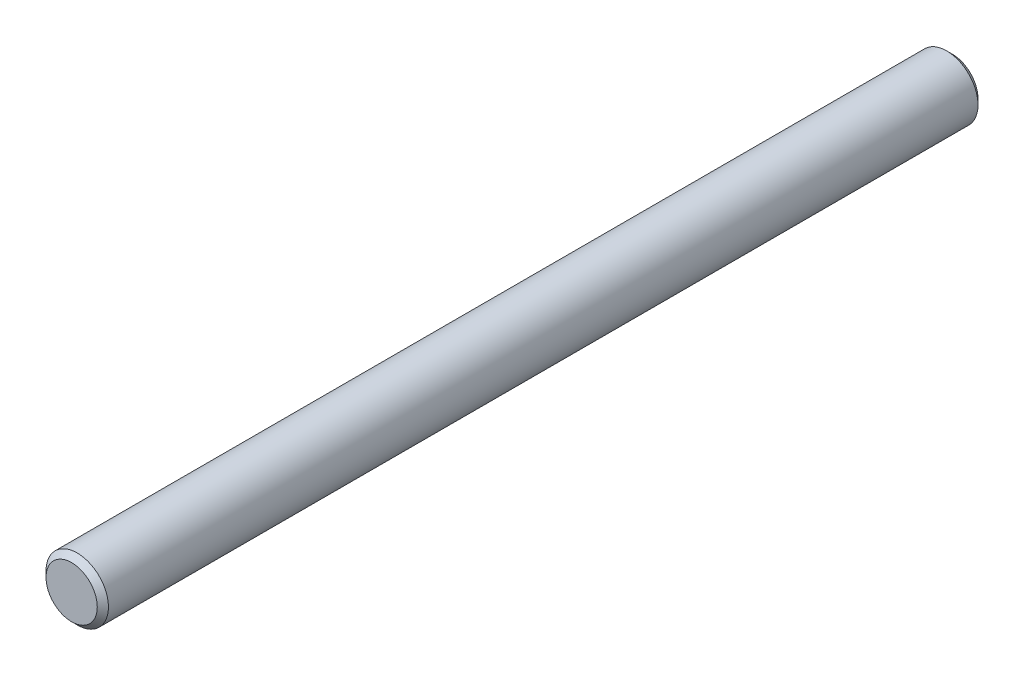
SolidWorks part; units mm, degrees
material "Chrome Stainless Steel"
ref_plane "Front Plane" through (0, 0, 0) normal (0, 0, 1) x (1, 0, 0)
ref_plane "Top Plane" through (0, 0, 0) normal (0, 1, 0) x (1, 0, 0)
ref_plane "Right Plane" through (0, 0, 0) normal (1, 0, 0) x (0, 0, -1)
sketch "Sketch1" plane through (0, 0, 0) normal (0, 0, 1) x (1, 0, 0)
  circle A0 centre (0, 0) radius 2.8
  dimension "D1" = 5.6
extrude "Boss-Extrude1" add sketch "Sketch1" against normal blind 79
chamfer "Chamfer1" distance 0.5 angle 45 2 edges at (2.8, 0, 0) (2.8, 0, -79)
